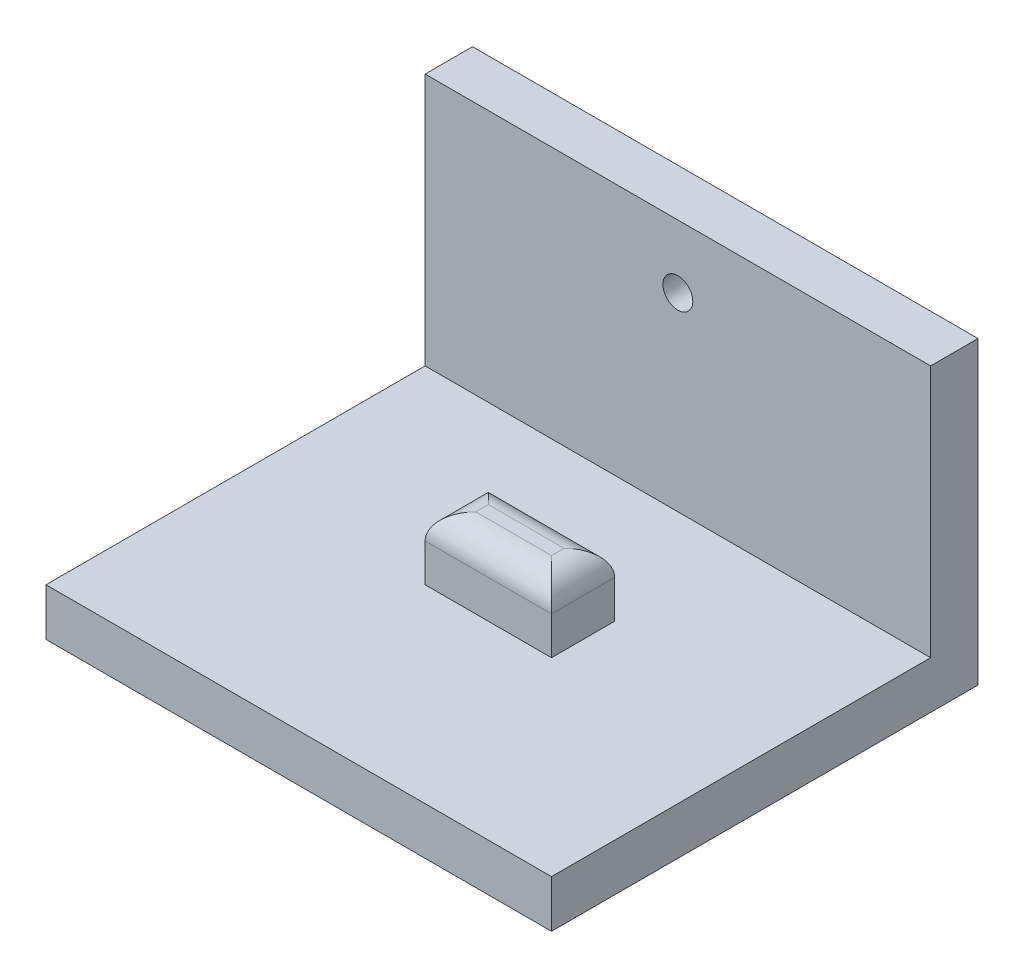
SolidWorks part; units mm, degrees
ref_plane "Front Plane" through (0, 0, 0) normal (0, 0, 1) x (1, 0, 0)
ref_plane "Top Plane" through (0, 0, 0) normal (0, 1, 0) x (1, 0, 0)
ref_plane "Right Plane" through (0, 0, 0) normal (1, 0, 0) x (0, 0, -1)
sketch "Sketch1" plane through (0, 0, 0) normal (1, 0, 0) x (0, 0, -1)
  line L0 (0, 0) -> (-42.8625, 0)
  line L1 (-42.8625, 0) -> (-42.8625, 4.7625)
  line L2 (-42.8625, 4.7625) -> (-4.7625, 4.7625)
  line L3 (-4.7625, 4.7625) -> (-4.7625, 30.1625)
  line L4 (-4.7625, 30.1625) -> (0, 30.1625)
  line L5 (0, 30.1625) -> (0, 0)
  dimension "D1" = 38.1
  dimension "D2" = 25.4
  dimension "D3" = 4.7625
extrude "Boss-Extrude1" add sketch "Sketch1" along normal blind 50.8
sketch "Sketch2" plane through (0, 4.7625, 0) normal (0, 1, 0) x (1, 0, 0)
  line L0 (50.8, -42.8625) -> (0, -42.8625) construction
  line L1 (19.05, -23.8125) -> (31.75, -23.8125)
  line L2 (19.05, -23.8125) -> (19.05, -17.4625)
  line L3 (19.05, -17.4625) -> (31.75, -17.4625)
  line L4 (31.75, -23.8125) -> (31.75, -17.4625)
  line L7 (50.8, -4.7625) -> (0, -4.7625) construction
  point P4 (25.4, -23.8125)
  point P7 (25.4, -42.8625)
  dimension "D1" = 6.35
  dimension "D2" = 12.7
  dimension "D3" = 12.7
extrude "Boss-Extrude2" add sketch "Sketch2" along normal blind 6.35
sketch "Sketch3" plane through (0, 0, 4.7625) normal (0, 0, 1) x (1, 0, 0)
  line L0 (50.8, 30.1625) -> (0, 30.1625) construction
  line L1 (50.8, 4.7625) -> (0, 4.7625) construction
  circle A0 centre (25.4, 23.8125) radius 1.5
  point P5 (25.4, 30.1625)
  dimension "D1" = 3
  dimension "D2" = 19.05
extrude "Cut-Extrude1" cut sketch "Sketch3" against normal through all
fillet "Fillet1" radius 2.54 4 edges at (25.4, 11.1125, 17.4625) (31.75, 11.1125, 20.6375) (25.4, 11.1125, 23.8125) (19.05, 11.1125, 20.6375)
